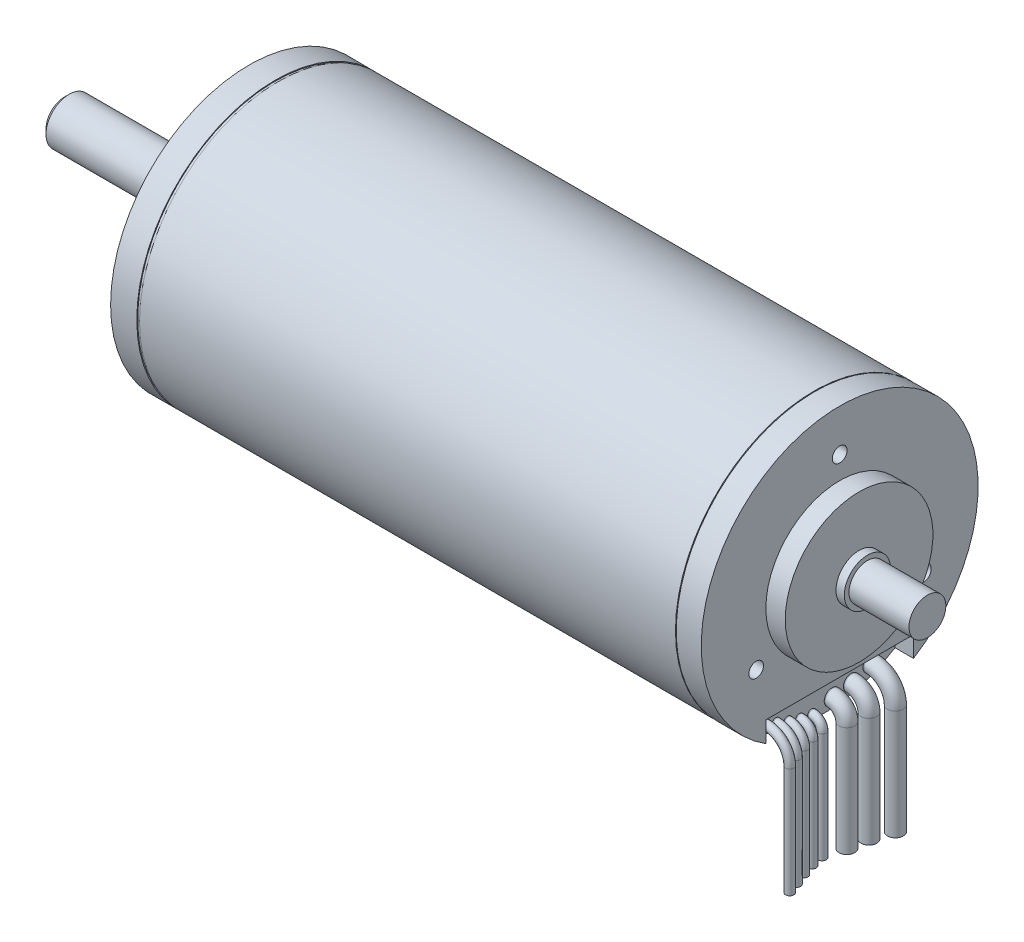
SolidWorks part; units mm, degrees
material "AISI 1020"
ref_plane "前视基准面" through (0, 0, 0) normal (0, 0, 1) x (1, 0, 0)
ref_plane "上视基准面" through (0, 0, 0) normal (0, 1, 0) x (1, 0, 0)
ref_plane "右视基准面" through (0, 0, 0) normal (1, 0, 0) x (0, 0, -1)
sketch "Model" plane through (0, 0, 0) normal (0, 0, 1) x (1, 0, 0)
  line L0 (20, 7) -> (18.8, 7)
  line L1 (84, 0) -> (20, 0)
  line L2 (86.1, 7) -> (84, 7)
  line L3 (87, 12.5) -> (86.1, 12.5)
  line L4 (98.5, 13) -> (87, 13)
  line L5 (98.5, 15) -> (98.5, 13)
  line L6 (0, 13) -> (0.5, 12.5)
  line L7 (0, 13) -> (0, 15)
  line L8 (18.8, 12.5) -> (0.5, 12.5)
  line L9 (0, 15) -> (98.5, 15)
  line L10 (18.8, 7) -> (18.8, 12.5)
  line L11 (20, 0) -> (20, 7)
  line L12 (84, 7) -> (84, 0)
  line L13 (86.1, 12.5) -> (86.1, 7)
  line L14 (87, 13) -> (87, 12.5)
revolve "旋转1" add sketch "Model" angle 360 about L9
sketch "草图2" plane through (20, 0, 0) normal (-1, 0, 0) x (0, 0, 1)
  line L0 (0, 26) -> (0, 4) construction
  line L2 (-11, 15) -> (11, 15) construction
  circle A0 centre (0, 15) radius 11 construction
  circle A1 centre (0, 26) radius 1.5
  circle A2 centre (11, 15) radius 1.5
  circle A3 centre (0, 4) radius 1.5
  circle A4 centre (-11, 15) radius 1.5
extrude "切除-拉伸1" cut sketch "草图2" against normal blind 4.5
sketch "草图3" plane through (84, 0, 0) normal (1, 0, 0) x (0, 0, -1)
  line L0 (0, 15) -> (0, 25.45) construction
  line L1 (0, 15) -> (-9.05, 9.775) construction
  line L2 (0, 15) -> (9.05, 9.775) construction
  circle A0 centre (0, 15) radius 10.45 construction
  circle A1 centre (0, 25.45) radius 0.8
  circle A2 centre (9.05, 9.775) radius 0.87
  circle A3 centre (-9.05, 9.775) radius 0.8
  dimension "D1" = 120
  dimension "D2" = 120
extrude "切除-拉伸2" cut sketch "草图3" against normal blind 2.4
sketch "草图4" plane through (84, 0, 0) normal (1, 0, 0) x (0, 0, -1)
  line L0 (0, 0) -> (0, 6.462) construction
  line L1 (0, 4.55) -> (-8, 4.55)
  line L2 (0, 4.55) -> (8, 4.55)
  line L3 (-8, 4.55) -> (-8, 2.3114)
  line L4 (8, 4.55) -> (8, 2.3114)
  circle A0 centre (0, 15) radius 10.45 construction
  circle A1 centre (0, 15) radius 15 construction
  arc A2 (-8, 2.3114) -> (8, 2.3114) centre (0, 15) ccw
extrude "切除-拉伸3" cut sketch "草图4" against normal blind 2
sketch "草图5" plane through (82, 0, 0) normal (1, 0, 0) x (0, 0, -1)
  line L0 (0, 0) -> (0, 6.2648) construction
  circle A0 centre (1.173, 1.1266) radius 0.8489
  circle A1 centre (-6.0754, 2.1869) radius 0.45
  circle A2 centre (3.2485, 1.4424) radius 0.845
  circle A3 centre (5.3691, 2.1869) radius 0.85
  circle A4 centre (-1.0378, 0.6528) radius 0.45
  circle A5 centre (-2.3463, 0.8744) radius 0.45
  circle A6 centre (-3.6322, 1.262) radius 0.45
  circle A7 centre (-4.918, 1.7583) radius 0.45
  dimension "D1" = 0.9
  dimension "D2" = 0.9
  dimension "D3" = 0.9
  dimension "D4" = 0.9
sketch "草图6" plane through (0, 0, 0) normal (0, 0, 1) x (1, 0, 0)
  line L0 (83.3926, -0.3846) -> (83.3926, -12.2821)
  line L1 (82.0926, 0.9154) -> (82, 0.9154)
  line L2 (82, 0.812) -> (82, 1.712) construction
  arc A1 (83.3926, -0.3846) -> (82.0926, 0.9154) centre (82.0926, -0.3846) ccw
  dimension "D2" = 1.3
sweep "扫描1" add profiles "草图5" path "草图6"
sketch "草图7" plane through (98.5, 0, 0) normal (1, 0, 0) x (0, 0, -1)
  circle A0 centre (0, 15) radius 2
extrude "切除-拉伸4" cut sketch "草图7" against normal blind 5
sketch "草图8" plane through (0, 0, 0) normal (0, 0, 1) x (1, 0, 0)
  line L0 (84, 30) -> (20, 30) construction
  line L1 (22.8363, 30) -> (23.1347, 30)
  line L2 (22.8363, 30) -> (22.8363, 29.9024)
  line L3 (22.8363, 29.9024) -> (23.1347, 29.9024)
  line L4 (23.1347, 30) -> (23.1347, 29.9024)
revolve "切除-旋转1" cut sketch "草图8" angle 360 about axis through (0, 15, 0) along (-1, 0, 0)
sketch "草图9" plane through (0, 0, 0) normal (0, 0, 1) x (1, 0, 0)
  line L1 (81.2022, 30.3813) -> (81.2908, 30.3813)
  line L2 (81.2022, 30.3813) -> (81.2022, 29.8786)
  line L3 (81.2022, 29.8786) -> (81.2908, 29.8786)
  line L4 (81.2908, 30.3813) -> (81.2908, 29.8786)
revolve "切除-旋转2" cut sketch "草图9" angle 360 about axis through (0, 15, 0) along (-1, 0, 0)
